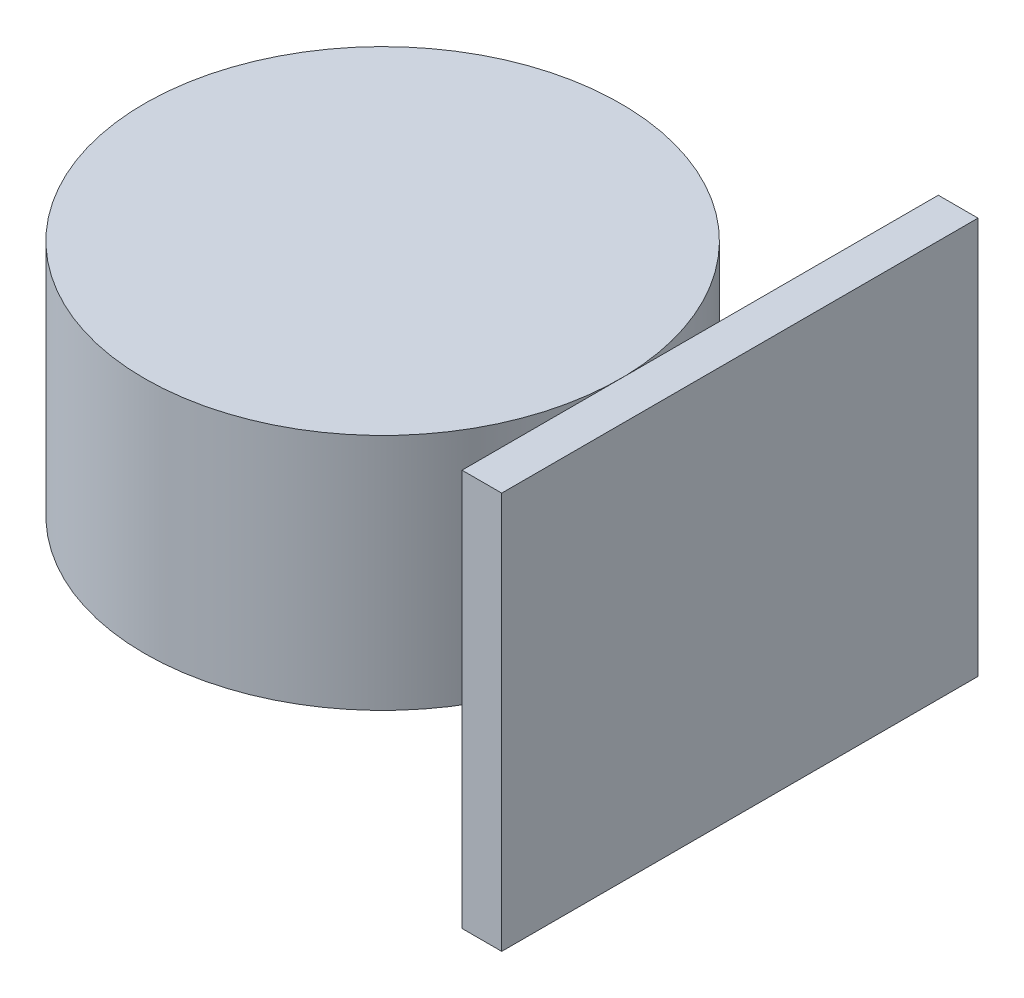
SolidWorks part; units mm, degrees
ref_plane "前视基准面" through (0, 0, 0) normal (0, 0, 1) x (1, 0, 0)
ref_plane "上视基准面" through (0, 0, 0) normal (0, 1, 0) x (1, 0, 0)
ref_plane "右视基准面" through (0, 0, 0) normal (1, 0, 0) x (0, 0, -1)
sketch "草图1" plane through (0, 0, 0) normal (0, 1, 0) x (1, 0, 0)
  circle A0 centre (0, 0) radius 30
  dimension "D1" = 60
extrude "凸台-拉伸1" add sketch "草图1" along normal mid plane 30
sketch "草图2" plane through (0, 0, 0) normal (1, 0, 0) x (0, 0, -1)
  line L0 (30, 15) -> (-30, 15) construction
  line L1 (-10, -10) -> (10, -10)
  line L2 (-10, -10) -> (-10, 10)
  line L3 (-10, 10) -> (10, 10)
  line L4 (10, -10) -> (10, 10)
  line L5 (0, 10) -> (0, -10) construction
  line L6 (-10, 0) -> (10, 0) construction
  point P0 (0, 0)
  dimension "D1" = 5
  dimension "D2" = 20
extrude "凸台-拉伸2" add sketch "草图2" along normal blind 40
sketch "草图3" plane through (40, 0, 0) normal (1, 0, 0) x (0, 0, -1)
  line L1 (-30, -25) -> (30, -25)
  line L2 (-30, -25) -> (-30, 25)
  line L3 (-30, 25) -> (30, 25)
  line L4 (30, -25) -> (30, 25)
  line L5 (0, 25) -> (0, -25) construction
  line L6 (-30, 0) -> (30, 0) construction
  point P0 (0, 0)
  dimension "D1" = 50
  dimension "D2" = 60
extrude "凸台-拉伸3" add sketch "草图3" along normal blind 5
